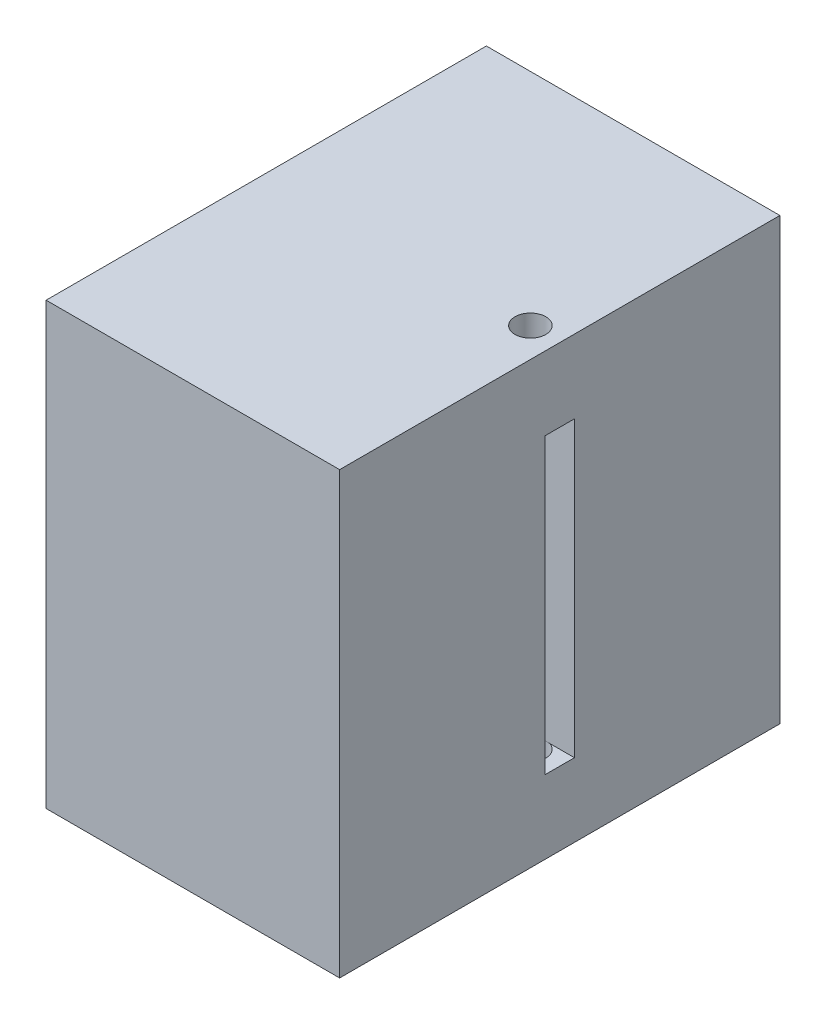
SolidWorks part; units mm, degrees
ref_plane "前视基准面" through (0, 0, 0) normal (0, 0, 1) x (1, 0, 0)
ref_plane "上视基准面" through (0, 0, 0) normal (0, 1, 0) x (1, 0, 0)
ref_plane "右视基准面" through (0, 0, 0) normal (1, 0, 0) x (0, 0, -1)
sketch "草图2" plane through (0, 0, 0) normal (0, 0, 1) x (1, 0, 0)
  line L1 (-51.5446, 25.6633) -> (-31.5446, 25.6633)
  line L2 (-51.5446, 25.6633) -> (-51.5446, -4.3367)
  line L3 (-51.5446, -4.3367) -> (-31.5446, -4.3367)
  line L4 (-31.5446, 25.6633) -> (-31.5446, -4.3367)
extrude "凸台-拉伸3" add sketch "草图2" along normal blind 30
sketch "草图3" plane through (0, -4.3367, 0) normal (0, -1, 0) x (1, 0, 0)
  line L0 (-51.5446, 30) -> (-51.5446, 0) construction
  line L1 (-31.5446, 0) -> (-51.5446, 0)
  line L2 (-31.5446, 0) -> (-31.5446, 30)
  line L3 (-31.5446, 30) -> (-51.5446, 30)
  line L4 (-51.5446, 0) -> (-51.5446, 30)
  line L5 (-51.5446, 30) -> (-31.5446, 30) construction
  line L6 (-31.5446, 15) -> (-35.5446, 15)
  line L8 (-31.5446, 15) -> (-35.5446, 15)
  line L9 (-31.5446, 15) -> (-31.5446, 13)
  line L10 (-31.5446, 13) -> (-35.5446, 13)
  line L11 (-35.5446, 15) -> (-35.5446, 13)
ref_plane "基准面4" through (0, 0.6633, 0) normal (0, -1, 0) x (-1, 0, 0)
sketch "草图4" plane through (0, 0.6633, 0) normal (0, -1, 0) x (-1, 0, 0)
  line L1 (27.5446, -16) -> (35.5446, -16)
  line L2 (27.5446, -16) -> (27.5446, -14)
  line L3 (27.5446, -14) -> (35.5446, -14)
  line L4 (35.5446, -16) -> (35.5446, -14)
  line L5 (27.5446, -16) -> (35.5446, -14) construction
  line L6 (27.5446, -14) -> (35.5446, -16) construction
  point P0 (31.5446, -15)
extrude "切除-拉伸1" cut sketch "草图4" against normal blind 20
sketch "草图5" plane through (0, -4.3367, 0) normal (0, -1, 0) x (1, 0, 0)
  line L0 (-31.5446, 14) -> (-51.5446, 14)
  line L1 (-51.5446, 0) -> (-51.5446, 30) construction
  line L2 (-35.5446, 15) -> (-31.5446, 15)
  circle A1 centre (-33.5446, 15) radius 1.05
extrude "切除-拉伸6" cut sketch "草图5" against normal blind 5 and the other way through all contours L2 A1 | L0 A1 L2 | L0 A1
sketch "草图7" plane through (0, 25.6633, 0) normal (0, 1, 0) x (1, 0, 0)
  line L0 (-35.5446, -15) -> (-31.5446, -15)
  circle A0 centre (-33.5446, -15) radius 1.05
extrude "切除-拉伸7" cut sketch "草图7" against normal blind 5 contours L0 A0 | L0 A0
